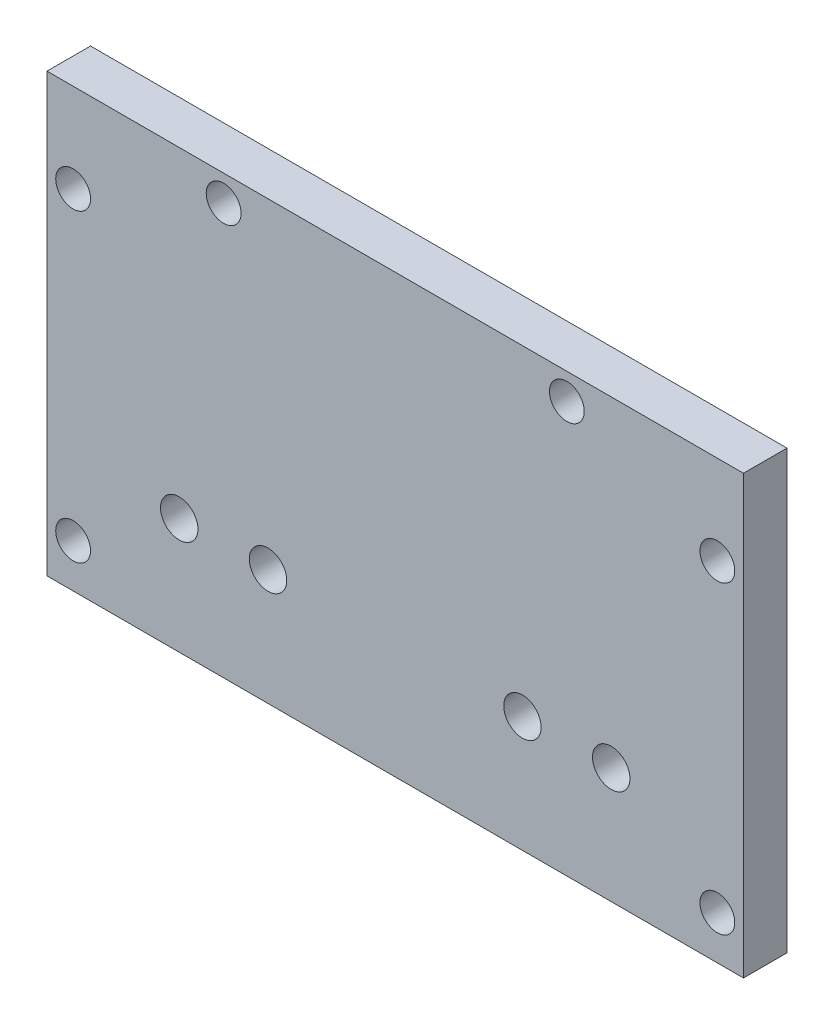
SolidWorks part; units mm, degrees
ref_plane "Front Plane" through (0, 0, 0) normal (0, 0, 1) x (1, 0, 0)
ref_plane "Top Plane" through (0, 0, 0) normal (0, 1, 0) x (1, 0, 0)
ref_plane "Right Plane" through (0, 0, 0) normal (1, 0, 0) x (0, 0, -1)
sketch "Sketch1" plane through (0, 0, 0) normal (0, 0, 1) x (1, 0, 0)
  line L1 (-40, 50.2112) -> (40, 50.2112)
  line L3 (40, 50.2112) -> (40, 0)
  line L4 (40, 0) -> (-40, 0)
  line L5 (-40, 0) -> (-40, 50.2112)
  circle A0 centre (14.6107, 13.3112) radius 2.15
  circle A1 centre (24.8107, 13.3112) radius 2.15
  circle A4 centre (-14.6107, 13.3112) radius 2.15
  circle A5 centre (-24.8107, 13.3112) radius 2.15
  dimension "D4" = 4.3
  dimension "D5" = 15.1893
  dimension "D6" = 13.3112
  dimension "D7" = 13.3112
  dimension "D8" = 25.3893
  dimension "D9" = 4.3
  dimension "D10" = 4.3
  dimension "D11" = 13.3112
  dimension "D12" = 25.3893
  dimension "D13" = 4.3
  dimension "D14" = 13.3112
  dimension "D15" = 15.1893
  dimension "D1" = 80
  dimension "D2" = 40
  dimension "D3" = 50.2112
extrude "Boss-Extrude1" add sketch "Sketch1" along normal blind 5
sketch "Sketch2" plane through (0, 0, 0) normal (0, 0, -1) x (-1, 0, 0)
  line L0 (0, 0) -> (0, 101.2317) construction
  line L1 (-40, 50.2112) -> (40, 50.2112) construction
  line L3 (-40, 50.2112) -> (40, 50.2112) construction
  line L4 (40, 50.2112) -> (40, 0) construction
  line L5 (40, 0) -> (-40, 0) construction
  line L6 (-40, 0) -> (-40, 50.2112) construction
  line L7 (40, 50.2112) -> (40, 0) construction
  circle A0 centre (19.7107, 47.2112) radius 2
  circle A1 centre (-19.7107, 47.2112) radius 2
  circle A2 centre (37, 40) radius 2
  circle A3 centre (-37, 40) radius 2
  circle A4 centre (37, 5) radius 2
  circle A5 centre (-37, 5) radius 2
  dimension "D1" = 4
  dimension "D2" = 3
  dimension "D3" = 20.2893
  dimension "D4" = 4
  dimension "D5" = 4
  dimension "D6" = 3
  dimension "D7" = 40
  dimension "D8" = 40
  dimension "D9" = 3
  dimension "D10" = 3
  dimension "D11" = 5
extrude "Cut-Extrude1" cut sketch "Sketch2" against normal blind 10
